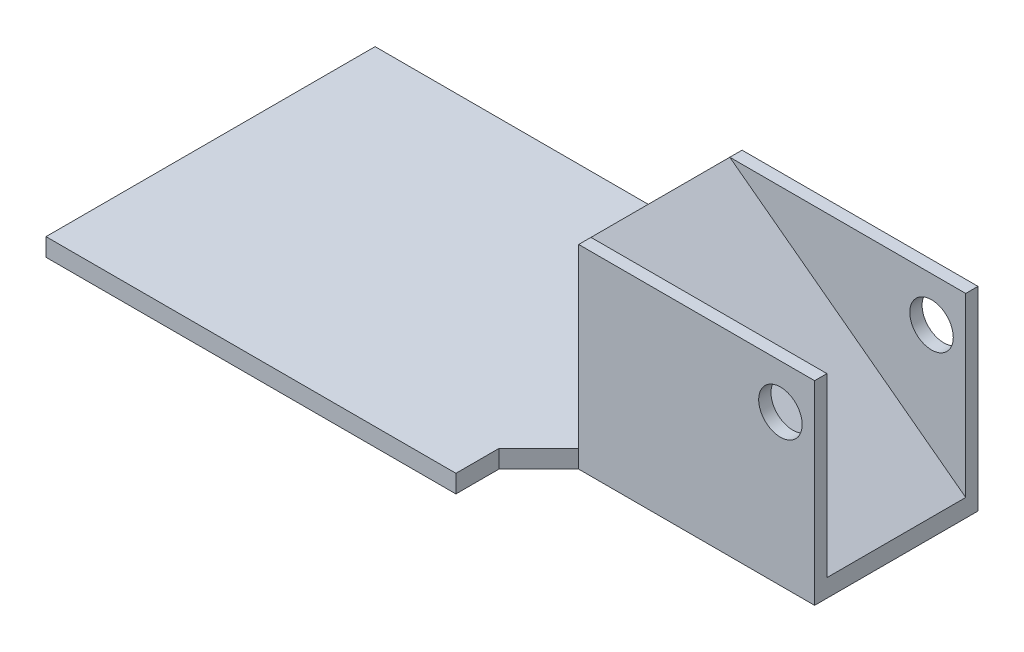
SolidWorks part; units mm, degrees
ref_plane "Front Plane" through (0, 0, 0) normal (0, 0, 1) x (1, 0, 0)
ref_plane "Top Plane" through (0, 0, 0) normal (0, 1, 0) x (1, 0, 0)
ref_plane "Right Plane" through (0, 0, 0) normal (1, 0, 0) x (0, 0, -1)
sketch "Sketch8" plane through (0, 0, 0) normal (0, 1, 0) x (1, 0, 0)
  line L0 (-44.9741, -2.9009) -> (-44.9741, -40.7469)
  line L1 (-44.9741, -40.7469) -> (2.1658, -40.7469)
  line L2 (2.1658, -40.7469) -> (2.1658, -35.808)
  line L3 (2.1658, -2.9009) -> (-44.9741, -2.9009)
  line L4 (2.1658, -7.8398) -> (6.7556, -12.4295)
  line L5 (2.1658, -7.8398) -> (2.1658, -2.9009)
  line L6 (6.7556, -31.2182) -> (2.1658, -35.808)
  line L7 (6.7556, -12.4295) -> (33.8879, -12.4295)
  line L8 (33.8879, -12.4295) -> (33.8879, -31.2182)
  line L9 (33.8879, -31.2182) -> (6.7556, -31.2182)
  line L10 (-44.9741, -21.8239) -> (33.8879, -21.8239) construction
  dimension "D1" = 37.846
  dimension "D2" = 47.1399
  dimension "D3" = 45
  dimension "D4" = 45
  dimension "D5" = 4.5898
  dimension "D6" = 18.923
  dimension "D7" = 4.9389
  dimension "D8" = 78.8619
extrude "Boss-Extrude6" add sketch "Sketch8" along normal blind 2.0599
sketch "Sketch9" plane through (0, 2.0599, 0) normal (0, 1, 0) x (1, 0, 0)
  line L0 (33.8879, -13.8418) -> (6.7556, -13.8418)
  line L1 (33.8879, -31.2182) -> (33.8879, -12.4295) construction
  line L2 (6.7556, -13.8418) -> (6.7556, -12.4295)
  line L3 (6.7556, -12.4295) -> (33.8879, -12.4295)
  line L4 (33.8879, -12.4295) -> (33.8879, -13.8418)
  line L5 (6.7556, -31.2182) -> (6.7556, -29.806)
  line L6 (6.7556, -29.806) -> (33.8879, -29.806)
  line L7 (33.8879, -29.806) -> (33.8879, -31.2182)
  line L8 (33.8879, -31.2182) -> (6.7556, -31.2182)
  dimension "D1" = 1.4122
  dimension "D2" = 1.4122
extrude "Boss-Extrude7" add sketch "Sketch9" along normal blind 20.32
sketch "Sketch10" plane through (0, 0, 31.2182) normal (0, 0, 1) x (1, 0, 0)
  line L0 (6.7556, 0) -> (33.8879, 0) construction
  line L1 (-44.9741, 2.0599) -> (-44.9741, 0) construction
  circle A0 centre (29.9559, 17.2847) radius 2.5006
  dimension "D2" = 74.93
  dimension "D1" = 17.2847
extrude "Cut-Extrude3" cut sketch "Sketch10" against normal blind 25.4
sketch "Sketch14" plane through (0, 0, 13.8418) normal (0, 0, 1) x (1, 0, 0)
  line L0 (6.7556, 22.3799) -> (33.8879, 2.0599)
  line L1 (6.7556, 22.3799) -> (6.7556, 19.8268)
  line L2 (6.7556, 22.3799) -> (6.7556, 2.0599) construction
  line L3 (6.7556, 19.8268) -> (30.5689, 2.0599)
  line L4 (30.5689, 2.0599) -> (33.8879, 2.0599)
extrude "Boss-Extrude10" add sketch "Sketch14" along normal blind 16.0299
sketch "Sketch15" plane through (0, 2.0599, 0) normal (0, 1, 0) x (1, 0, 0)
  line L0 (6.7556, -29.806) -> (6.7556, -13.8418) construction
  line L1 (-44.9741, -40.7469) -> (6.7556, -40.7469)
  line L2 (-44.9741, -40.7469) -> (-44.9741, -2.9009)
  line L3 (-44.9741, -2.9009) -> (6.7556, -2.9009)
  line L4 (6.7556, -40.7469) -> (6.7556, -2.9009)
  line L5 (2.1658, -2.9009) -> (-44.9741, -2.9009) construction
